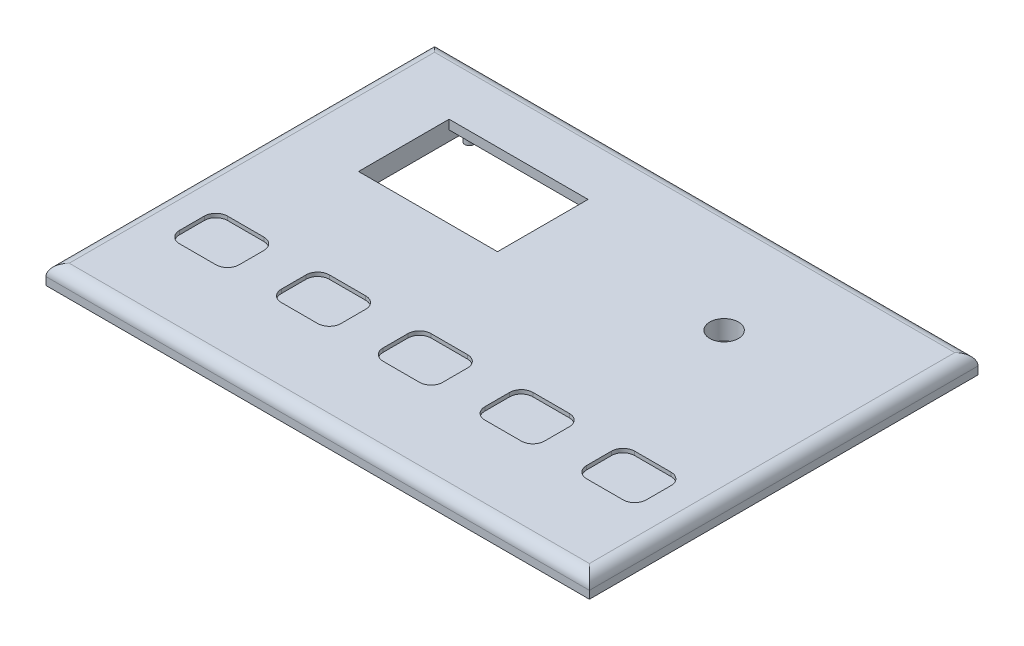
SolidWorks part; units mm, degrees
ref_plane "Front Plane" through (0, 0, 0) normal (0, 0, 1) x (1, 0, 0)
ref_plane "Top Plane" through (0, 0, 0) normal (0, 1, 0) x (1, 0, 0)
ref_plane "Right Plane" through (0, 0, 0) normal (1, 0, 0) x (0, 0, -1)
sketch "Sketch1" plane through (0, 0, 0) normal (0, 1, 0) x (1, 0, 0)
  line L0 (-64.0959, -44.911) -> (65.5041, -44.911) construction
  line L1 (-69.4959, -50.311) -> (70.9041, -50.311)
  line L2 (-69.4959, -50.311) -> (-69.4959, 50.089)
  line L3 (-69.4959, 50.089) -> (70.9041, 50.089)
  line L4 (70.9041, -50.311) -> (70.9041, 50.089)
  line L7 (65.5041, -44.911) -> (65.5041, 44.689) construction
  line L8 (-64.0959, 44.689) -> (65.5041, 44.689) construction
  line L9 (-64.0959, -44.911) -> (-64.0959, 44.689) construction
  line L10 (-64.0959, -22.511) -> (65.5041, -22.511) construction
  line L29 (-48.1959, -40.411) -> (-39.6959, -40.411)
  line L30 (-69.4959, -0.111) -> (70.9041, -0.111) construction
  line L31 (0.7041, -50.311) -> (0.7041, 50.089) construction
  line L32 (-64.0959, -16.011) -> (-39.6959, -16.011)
  line L33 (-49.6459, 39.239) -> (-13.7459, 39.239)
  line L34 (-49.6459, 39.239) -> (-49.6459, 5.339)
  line L35 (-49.6459, 5.339) -> (-13.7459, 5.339)
  line L36 (-13.7459, 39.239) -> (-13.7459, 5.339)
  line L37 (-49.6459, 39.239) -> (-13.7459, 5.339) construction
  line L38 (-49.6459, 5.339) -> (-13.7459, 39.239) construction
  line L39 (-49.6459, 10.589) -> (-13.7459, 10.589)
  line L40 (-49.6459, 10.589) -> (-49.6459, 33.989)
  line L41 (-49.6459, 33.989) -> (-13.7459, 33.989)
  line L42 (-13.7459, 10.589) -> (-13.7459, 33.989)
  line L43 (-49.6459, 10.589) -> (-13.7459, 33.989) construction
  line L44 (-49.6459, 33.989) -> (-13.7459, 10.589) construction
  line L45 (-64.0959, -16.011) -> (-64.0959, -40.411)
  line L46 (-64.0959, -40.411) -> (-55.5959, -40.411)
  line L47 (-39.6959, -16.011) -> (-39.6959, -40.411)
  line L49 (-55.5959, -40.411) -> (-55.5959, -35.411)
  line L50 (-55.5959, -35.411) -> (-48.1959, -35.411)
  line L51 (-48.1959, -40.411) -> (-48.1959, -35.411)
  line L52 (-37.7959, -40.411) -> (-29.2959, -40.411)
  line L53 (-29.2959, -40.411) -> (-29.2959, -35.411)
  line L54 (-29.2959, -35.411) -> (-21.8959, -35.411)
  line L55 (-21.8959, -40.411) -> (-21.8959, -35.411)
  line L56 (-21.8959, -40.411) -> (-13.3959, -40.411)
  line L57 (-13.3959, -16.011) -> (-13.3959, -40.411)
  line L58 (-37.7959, -16.011) -> (-13.3959, -16.011)
  line L59 (-37.7959, -16.011) -> (-37.7959, -40.411)
  line L60 (-11.4959, -40.411) -> (-2.9959, -40.411)
  line L61 (-2.9959, -40.411) -> (-2.9959, -35.411)
  line L62 (-2.9959, -35.411) -> (4.4041, -35.411)
  line L63 (4.4041, -40.411) -> (4.4041, -35.411)
  line L64 (4.4041, -40.411) -> (12.9041, -40.411)
  line L65 (12.9041, -16.011) -> (12.9041, -40.411)
  line L66 (-11.4959, -16.011) -> (12.9041, -16.011)
  line L67 (-11.4959, -16.011) -> (-11.4959, -40.411)
  line L68 (14.8041, -40.411) -> (23.3041, -40.411)
  line L69 (23.3041, -40.411) -> (23.3041, -35.411)
  line L70 (23.3041, -35.411) -> (30.7041, -35.411)
  line L71 (30.7041, -40.411) -> (30.7041, -35.411)
  line L72 (30.7041, -40.411) -> (39.2041, -40.411)
  line L73 (39.2041, -16.011) -> (39.2041, -40.411)
  line L74 (14.8041, -16.011) -> (39.2041, -16.011)
  line L75 (14.8041, -16.011) -> (14.8041, -40.411)
  line L76 (41.1041, -40.411) -> (49.6041, -40.411)
  line L77 (49.6041, -40.411) -> (49.6041, -35.411)
  line L78 (49.6041, -35.411) -> (57.0041, -35.411)
  line L79 (57.0041, -40.411) -> (57.0041, -35.411)
  line L80 (57.0041, -40.411) -> (65.5041, -40.411)
  line L81 (65.5041, -16.011) -> (65.5041, -40.411)
  line L82 (41.1041, -16.011) -> (65.5041, -16.011)
  line L83 (41.1041, -16.011) -> (41.1041, -40.411)
  line L84 (-64.0959, -40.411) -> (-37.7959, -40.411) construction
  line L85 (-51.8959, -16.011) -> (-51.8959, -40.411) construction
  line L86 (-33.2959, -25.711) -> (-33.2959, -19.311)
  line L87 (-56.5959, -28.711) -> (-47.1959, -28.711)
  line L88 (-59.5959, -25.711) -> (-59.5959, -19.311)
  line L89 (-56.5959, -16.311) -> (-47.1959, -16.311)
  line L90 (-44.1959, -25.711) -> (-44.1959, -19.311)
  line L91 (-59.5959, -28.711) -> (-44.1959, -16.311) construction
  line L92 (-59.5959, -16.311) -> (-44.1959, -28.711) construction
  line L93 (-30.2959, -28.711) -> (-20.8959, -28.711)
  line L94 (-17.8959, -25.711) -> (-17.8959, -19.311)
  line L95 (-30.2959, -16.311) -> (-20.8959, -16.311)
  line L96 (-6.9959, -25.711) -> (-6.9959, -19.311)
  line L97 (-3.9959, -28.711) -> (5.4041, -28.711)
  line L98 (8.4041, -25.711) -> (8.4041, -19.311)
  line L99 (-3.9959, -16.311) -> (5.4041, -16.311)
  line L100 (19.3041, -25.711) -> (19.3041, -19.311)
  line L101 (22.3041, -28.711) -> (31.7041, -28.711)
  line L102 (34.7041, -25.711) -> (34.7041, -19.311)
  line L103 (22.3041, -16.311) -> (31.7041, -16.311)
  line L104 (45.6041, -25.711) -> (45.6041, -19.311)
  line L105 (48.6041, -28.711) -> (58.0041, -28.711)
  line L106 (61.0041, -25.711) -> (61.0041, -19.311)
  line L107 (48.6041, -16.311) -> (58.0041, -16.311)
  line L108 (-59.5959, -25.711) -> (-33.2959, -25.711) construction
  circle A5 centre (33.1041, 22.289) radius 3.7
  arc A7 (-56.5959, -28.711) -> (-59.5959, -25.711) centre (-56.5959, -25.711) cw
  arc A8 (-47.1959, -28.711) -> (-44.1959, -25.711) centre (-47.1959, -25.711) ccw
  arc A9 (-44.1959, -19.311) -> (-47.1959, -16.311) centre (-47.1959, -19.311) ccw
  arc A10 (-56.5959, -16.311) -> (-59.5959, -19.311) centre (-56.5959, -19.311) ccw
  arc A11 (-30.2959, -16.311) -> (-33.2959, -19.311) centre (-30.2959, -19.311) ccw
  arc A12 (-30.2959, -28.711) -> (-33.2959, -25.711) centre (-30.2959, -25.711) cw
  arc A13 (-20.8959, -28.711) -> (-17.8959, -25.711) centre (-20.8959, -25.711) ccw
  arc A14 (-17.8959, -19.311) -> (-20.8959, -16.311) centre (-20.8959, -19.311) ccw
  arc A15 (-3.9959, -16.311) -> (-6.9959, -19.311) centre (-3.9959, -19.311) ccw
  arc A16 (-3.9959, -28.711) -> (-6.9959, -25.711) centre (-3.9959, -25.711) cw
  arc A17 (5.4041, -28.711) -> (8.4041, -25.711) centre (5.4041, -25.711) ccw
  arc A18 (8.4041, -19.311) -> (5.4041, -16.311) centre (5.4041, -19.311) ccw
  arc A19 (22.3041, -16.311) -> (19.3041, -19.311) centre (22.3041, -19.311) ccw
  arc A20 (22.3041, -28.711) -> (19.3041, -25.711) centre (22.3041, -25.711) cw
  arc A21 (31.7041, -28.711) -> (34.7041, -25.711) centre (31.7041, -25.711) ccw
  arc A22 (34.7041, -19.311) -> (31.7041, -16.311) centre (31.7041, -19.311) ccw
  arc A23 (48.6041, -16.311) -> (45.6041, -19.311) centre (48.6041, -19.311) ccw
  arc A24 (48.6041, -28.711) -> (45.6041, -25.711) centre (48.6041, -25.711) cw
  arc A25 (58.0041, -28.711) -> (61.0041, -25.711) centre (58.0041, -25.711) ccw
  arc A26 (61.0041, -19.311) -> (58.0041, -16.311) centre (58.0041, -19.311) ccw
  point P0 (0, 0)
  point P24 (-51.8959, -22.511)
  point P46 (-31.6959, 22.289)
  point P51 (-31.6959, 22.289)
  dimension "D6" = 15.4
  dimension "D17" = 23.4
  dimension "D18" = 7.4
  dimension "D7" = 24.4
  dimension "D5" = 12.2
  dimension "D26" = 3
  dimension "D1" = 140.4
  dimension "D2" = 100.4
  dimension "D3" = 5.4
  dimension "D8" = 24.4
  dimension "D10" = 8.5
  dimension "D13" = 37.8
  dimension "D14" = 27.8
  dimension "D15" = 35.9
  dimension "D16" = 33.9
  dimension "D19" = 32.4
  dimension "D20" = 27.8
  dimension "D4" = 22.4
  dimension "D9" = 12.4
  dimension "D22" = 8.5
  dimension "D23" = 5
  dimension "D25" = 26.3
  dimension "D28" = 26.3
  dimension "D11" = 50.2
  dimension "D12" = 70.2
  dimension "D24" = 5
  dimension "D27" = 5
extrude "Boss-Extrude1" add sketch "Sketch1" along normal blind 5
fillet "Fillet1" radius 3 4 edges at (0.7041, 5, 50.311) (-69.4959, 5, 0.111) (0.7041, 5, -50.089) (70.9041, 5, 0.111)
sketch "Sketch3" plane through (0, 5, 0) normal (0, 1, 0) x (1, 0, 0)
  line L0 (-13.7459, 39.239) -> (-13.7459, 5.339) construction
  line L1 (-49.6459, 39.239) -> (-13.7459, 39.239)
  line L2 (-49.6459, 39.239) -> (-49.6459, 33.989)
  line L3 (-49.6459, 33.989) -> (-13.7459, 33.989)
  line L4 (-13.7459, 39.239) -> (-13.7459, 33.989)
  line L6 (-49.6459, 5.339) -> (-13.7459, 5.339)
  line L7 (-49.6459, 5.339) -> (-49.6459, 10.589)
  line L8 (-49.6459, 10.589) -> (-13.7459, 10.589)
  line L9 (-13.7459, 5.339) -> (-13.7459, 10.589)
  dimension "D1" = 5.25
  dimension "D2" = 5.25
extrude "Boss-Extrude2" add sketch "Sketch3" against normal blind 2.4
sketch "Sketch4" plane through (0, 0, 0) normal (0, -1, 0) x (1, 0, 0)
  line L1 (-49.6459, -39.239) -> (-13.7459, -39.239) construction
  line L2 (-16.4459, -39.239) -> (-16.4459, -5.339)
  line L3 (-16.4459, -39.239) -> (-16.4459, -5.339) construction
  line L6 (-31.6959, -39.239) -> (-31.6959, -5.339)
  line L7 (-31.6959, -39.239) -> (-31.6959, -5.339) construction
  line L9 (-49.6459, -22.289) -> (-13.7459, -22.289)
  line L10 (-49.6459, -22.289) -> (-13.7459, -22.289) construction
  line L13 (-13.7459, -5.339) -> (-13.7459, -10.589) construction
  line L14 (-49.6459, -5.339) -> (-13.7459, -5.339) construction
  circle A0 centre (-16.4459, -36.539) radius 1.2
  circle A4 centre (-46.9459, -36.539) radius 1.2
  circle A5 centre (-16.4459, -7.539) radius 1.2
  circle A6 centre (-46.9459, -7.539) radius 1.2
  dimension "D3" = 2.4
  dimension "D6" = 2.4
  dimension "D2" = 2.7
  dimension "D7" = 2.7
  dimension "D8" = 2.2
  dimension "D1" = 2.7
  dimension "D4" = 17.95
  dimension "D5" = 16.95
extrude "Boss-Extrude3" add sketch "Sketch4" along normal up to surface (2.6 mm away) from surface at -2.6 up to face at (33.1041, 0, -18.589) starting at face at (-31.6959, 2.6, -7.964)
sketch "Sketch6" plane through (0, 0, 0) normal (0, -1, 0) x (1, 0, 0)
  line L1 (-39.6959, 16.011) -> (-64.0959, 16.011)
  line L2 (-39.6959, 16.011) -> (-39.6959, 40.411)
  line L3 (-39.6959, 40.411) -> (-64.0959, 40.411)
  line L4 (-64.0959, 16.011) -> (-64.0959, 40.411)
  line L5 (-39.6959, 16.011) -> (-64.0959, 40.411) construction
  line L6 (-56.5959, 22.511) -> (-47.1959, 22.511)
  line L7 (-71.0193, 22.511) -> (88.0771, 22.511) construction
  line L8 (-39.6959, 40.411) -> (-64.0959, 16.011) construction
  line L9 (-56.5959, 16.311) -> (-47.1959, 16.311) construction
  point P0 (-51.8959, 28.211)
  point P11 (-51.8959, 16.311)
  dimension "D1" = 6.5
  dimension "D3" = 24.4
  dimension "D4" = 24.4
  dimension "D5" = 12.2
  dimension "D2" = 6.2
extrude "Cut-Extrude1" cut sketch "Sketch6" against normal blind 3
pattern_linear "LPattern1" count 5 spacing 26.3 along (1, 0, 0) of "Cut-Extrude1"
sketch "Sketch7" plane through (0, 3, 0) normal (0, -1, 0) x (1, 0, 0)
  line L3 (-61.4959, 40.411) -> (-61.4959, 16.011)
  line L4 (-61.4959, 40.411) -> (-61.4959, 16.011) construction
  line L6 (-39.6959, 37.811) -> (-64.0959, 37.811)
  line L7 (-39.6959, 37.811) -> (-64.0959, 37.811) construction
  line L9 (-51.8959, 40.411) -> (-51.8959, 16.011)
  line L10 (-51.8959, 40.411) -> (-51.8959, 16.011) construction
  line L12 (-39.6959, 28.211) -> (-64.0959, 28.211)
  line L13 (-39.6959, 28.211) -> (-64.0959, 28.211) construction
  circle A0 centre (-61.4959, 37.811) radius 1.1
  circle A1 centre (-42.2959, 37.811) radius 1.1
  circle A2 centre (-61.4959, 18.611) radius 1.1
  circle A3 centre (-42.2959, 18.611) radius 1.1
  dimension "D3" = 2.2
  dimension "D1" = 2.6
  dimension "D2" = 2.6
  dimension "D4" = 12.2
  dimension "D5" = 12.2
extrude "Boss-Extrude4" add sketch "Sketch7" along normal up to surface (3 mm away) up to face at (-25.5959, 0, 28.211)
pattern_linear "LPattern2" count 5 spacing 26.3 along (1, 0, 0) of "Boss-Extrude4"
sketch "Sketch9" plane through (0, 3, 0) normal (0, -1, 0) x (1, 0, 0)
  line L0 (-59.5959, 19.311) -> (-59.5959, 25.711) construction
  line L1 (-59.5959, 16.311) -> (-44.1959, 16.311)
  line L2 (-59.5959, 16.311) -> (-59.5959, 28.711)
  line L3 (-59.5959, 28.711) -> (-44.1959, 28.711)
  line L4 (-44.1959, 16.311) -> (-44.1959, 28.711)
  line L5 (-59.5959, 16.311) -> (-44.1959, 28.711) construction
  line L6 (-59.5959, 28.711) -> (-44.1959, 16.311) construction
  line L7 (-44.1959, 19.311) -> (-44.1959, 25.711) construction
  line L8 (-47.1959, 28.711) -> (-56.5959, 28.711) construction
  line L9 (-47.1959, 16.311) -> (-56.5959, 16.311) construction
  point P0 (-51.8959, 22.511)
extrude "Boss-Extrude5" add sketch "Sketch9" against normal blind 1
pattern_linear "LPattern3" count 5 spacing 26.3 along (1, 0, 0) of "Boss-Extrude5"
